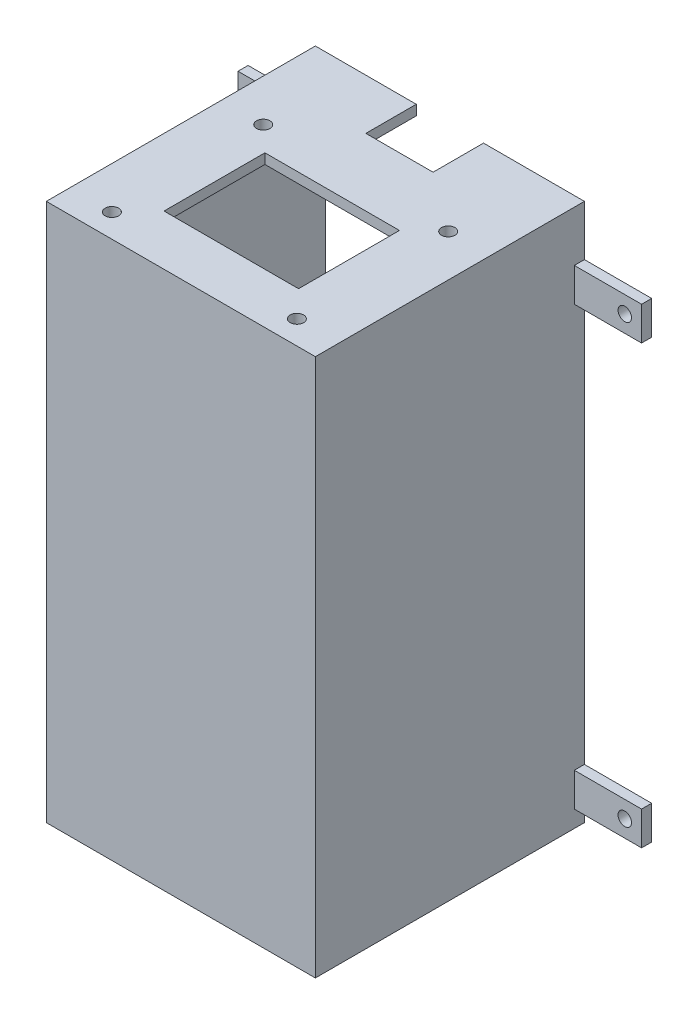
SolidWorks part; units mm, degrees
ref_plane "Front Plane" through (0, 0, 0) normal (0, 0, 1) x (1, 0, 0)
ref_plane "Top Plane" through (0, 0, 0) normal (0, 1, 0) x (1, 0, 0)
ref_plane "Right Plane" through (0, 0, 0) normal (1, 0, 0) x (0, 0, -1)
sketch "Sketch1" plane through (0, 0, 0) normal (0, 0, 1) x (1, 0, 0)
  line L1 (40, -80) -> (-40, -80)
  line L2 (40, -80) -> (40, 80)
  line L3 (40, 80) -> (-40, 80)
  line L4 (-40, -80) -> (-40, 80)
  line L5 (40, -80) -> (-40, 80) construction
  line L6 (40, 80) -> (-40, -80) construction
  point P0 (0, 0)
  dimension "D1" = 160
  dimension "D2" = 80
extrude "Boss-Extrude1" add sketch "Sketch1" along normal blind 80
shell "Shell1" thickness 3
sketch "Sketch2" plane through (0, 80, 0) normal (0, 1, 0) x (1, 0, 0)
  line L0 (40, -80) -> (-40, -80) construction
  line L1 (20, -65) -> (-20, -65)
  line L2 (20, -65) -> (20, -35)
  line L3 (20, -35) -> (-20, -35)
  line L4 (-20, -65) -> (-20, -35)
  line L5 (20, -65) -> (-20, -35) construction
  line L6 (20, -35) -> (-20, -65) construction
  point P0 (0, -50)
  point P5 (0, 0)
  dimension "D1" = 15
  dimension "D2" = 30
  dimension "D3" = 40
extrude "Cut-Extrude1" cut sketch "Sketch2" against normal blind 70
sketch "Sketch3" plane through (0, 80, 0) normal (0, 1, 0) x (1, 0, 0)
  line L0 (40, 0) -> (-40, 0) construction
  line L1 (10, -15) -> (-10, -15)
  line L2 (10, -15) -> (10, 0)
  line L3 (10, 0) -> (-10, 0)
  line L4 (-10, -15) -> (-10, 0)
  line L5 (10, -15) -> (-10, 0) construction
  line L6 (10, 0) -> (-10, -15) construction
  point P0 (0, -7.5)
  point P7 (0, 0)
  dimension "D1" = 20
  dimension "D2" = 15
extrude "Cut-Extrude2" cut sketch "Sketch3" against normal blind 70
sketch "Sketch4" plane through (0, -80, 0) normal (0, -1, 0) x (-1, 0, 0)
  line L0 (40, 0) -> (-40, 0) construction
  line L1 (-35, -15) -> (35, -15)
  line L2 (-35, -15) -> (-35, 0)
  line L3 (-35, 0) -> (35, 0)
  line L4 (35, -15) -> (35, 0)
  line L5 (-35, -15) -> (35, 0) construction
  line L6 (-35, 0) -> (35, -15) construction
  point P0 (0, -7.5)
  point P7 (0, 0)
  dimension "D1" = 15
  dimension "D2" = 70
extrude "Cut-Extrude3" cut sketch "Sketch4" against normal blind 70
sketch "Sketch5" plane through (0, 0, 0) normal (0, 0, -1) x (-1, 0, 0)
  line L0 (40, 80) -> (40, -80) construction
  line L1 (40, 65) -> (60, 65)
  line L2 (40, 65) -> (40, 55)
  line L3 (40, 55) -> (60, 55)
  line L4 (60, 65) -> (60, 55)
  line L5 (40, 65) -> (60, 55) construction
  line L6 (40, 55) -> (60, 65) construction
  line L7 (10, 80) -> (40, 80) construction
  line L8 (40, -65) -> (60, -65)
  line L9 (40, -65) -> (40, -75)
  line L10 (40, -75) -> (60, -75)
  line L11 (60, -65) -> (60, -75)
  line L12 (40, -65) -> (60, -75) construction
  line L13 (40, -75) -> (60, -65) construction
  line L14 (40, -80) -> (35, -80) construction
  circle A0 centre (55, 60) radius 2
  circle A1 centre (55, -70) radius 2
  point P4 (50, 60)
  point P11 (50, -70)
  point P16 (0, 0)
  point P17 (37.1098, 37.2803)
  point P18 (41.9906, 32.4261)
  point P19 (0, 0)
  point P20 (39.1289, 37.3398)
  point P21 (0, 0)
  point P22 (40, 36.2852)
  point P23 (40, 36.2748)
  point P24 (40, 36.4441)
  point P25 (0, 0)
  point P27 (45, -34.5131)
  point P32 (50, -60)
  dimension "D1" = 4
  dimension "D4" = 15
  dimension "D6" = 15
  dimension "D2" = 10
  dimension "D3" = 20
  dimension "D5" = 5
extrude "Boss-Extrude2" add sketch "Sketch5" against normal blind 3
mirror "Mirror1" about plane through (0, 0, 0) normal (1, 0, 0) of "Boss-Extrude2"
sketch "Sketch6" plane through (0, 80, 0) normal (0, 1, 0) x (1, 0, 0)
  line L10 (40, -80) -> (-40, -80) construction
  line L18 (-27.5, -73) -> (27.5, -73) construction
  line L19 (-27.5, -28) -> (-27.5, -73) construction
  line L20 (27.5, -28) -> (-27.5, -28) construction
  line L21 (27.5, -73) -> (27.5, -28) construction
  circle A0 centre (-27.5, -28) radius 2
  circle A2 centre (27.5, -28) radius 2
  circle A3 centre (27.5, -73) radius 2
  circle A4 centre (-27.5, -73) radius 2
  point P4 (0, -28)
  dimension "D2" = 4
  dimension "D1" = 55
  dimension "D3" = 45
  dimension "D4" = 7
extrude "Cut-Extrude4" cut sketch "Sketch6" against normal blind 3
